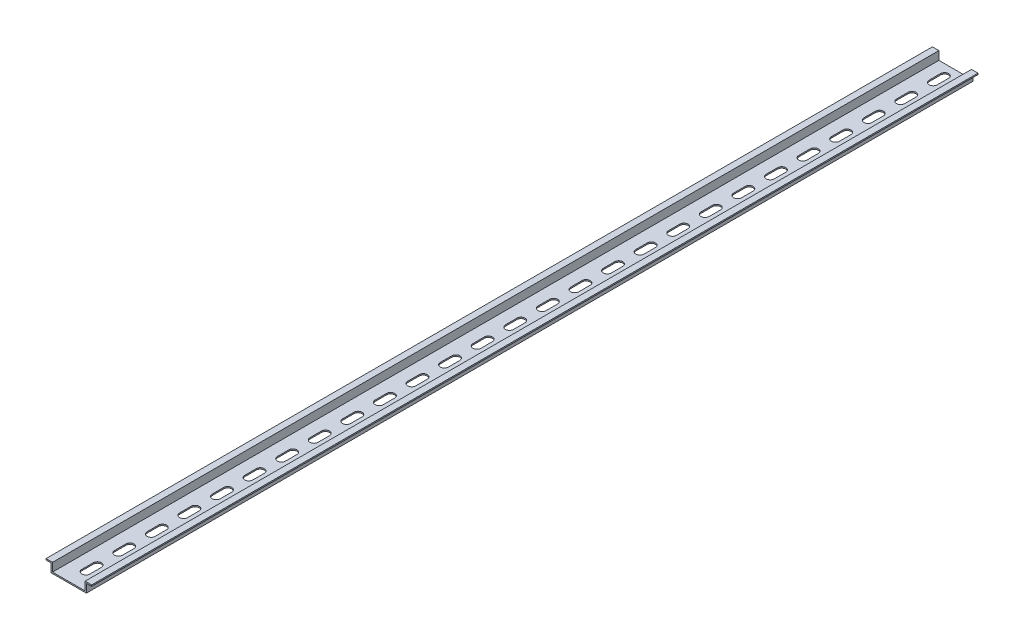
SolidWorks part; units mm, degrees
material "1060 Alloy"
ref_plane "Front Plane" through (0, 0, 0) normal (0, 0, 1) x (1, 0, 0)
ref_plane "Top Plane" through (0, 0, 0) normal (0, 1, 0) x (1, 0, 0)
ref_plane "Right Plane" through (0, 0, 0) normal (1, 0, 0) x (0, 0, -1)
sketch "Sketch1" plane through (0, 0, 0) normal (0, 0, 1) x (1, 0, 0)
  line L0 (0, 0) -> (13.5, 0)
  line L1 (13.5, 0) -> (13.5, 6.5)
  line L2 (13.5, 6.5) -> (17.5, 6.5)
  line L3 (17.5, 6.5) -> (17.5, 7.5)
  line L4 (17.5, 7.5) -> (12.5, 7.5)
  line L5 (12.5, 7.5) -> (12.5, 1)
  line L6 (12.5, 1) -> (0, 1)
  line L7 (0, 1) -> (0, 0)
  line L8 (13.5, 6.5) -> (12.5, 6.5) construction
  dimension "D1" = 1
  dimension "D2" = 13.5
  dimension "D3" = 6.5
  dimension "D4" = 4
extrude "Boss-Extrude1" add sketch "Sketch1" along normal blind 680
sketch "Sketch2" plane through (0, 0, 0) normal (0, 1, 0) x (1, 0, 0)
  line L0 (0, -8.1) -> (0, -16.9) construction
  line L1 (3.1, -8.1) -> (3.1, -16.9)
  line L2 (-3.1, -8.1) -> (-3.1, -16.9)
  line L3 (0, -680) -> (0, 0) construction
  arc A0 (3.1, -8.1) -> (-3.1, -8.1) centre (0, -8.1) ccw
  arc A1 (-3.1, -16.9) -> (3.1, -16.9) centre (0, -16.9) ccw
  point P2 (0, -12.5)
  dimension "D2" = 3.1
  dimension "D1" = 8.8
  dimension "D3" = 12.5
extrude "Cut-Extrude1" cut sketch "Sketch2" along normal through all
pattern_linear "LPattern1" count 27 spacing 25 along (0, 0, 1) of "Cut-Extrude1"
mirror "Mirror2" about plane through (0, 0, 0) normal (1, 0, 0) of "LPattern1", "Cut-Extrude1", "Boss-Extrude1"
ref_plane "Plane1" through (0, 0, 340) normal (0, 0, 1) x (1, 0, 0)
